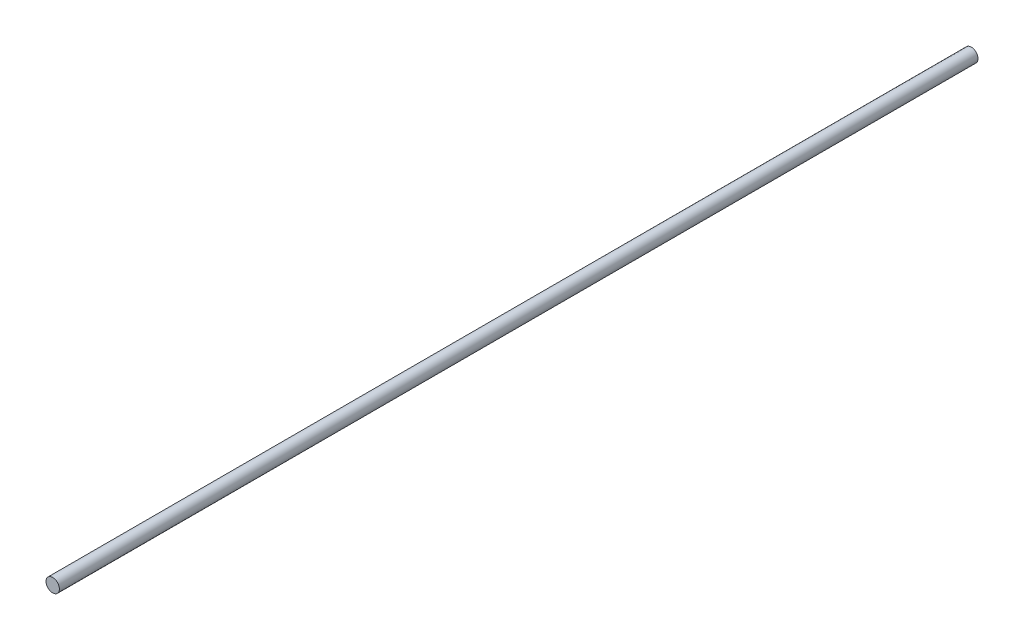
SolidWorks part; units mm, degrees
ref_plane "Спереди" through (0, 0, 0) normal (0, 0, 1) x (1, 0, 0)
ref_plane "Сверху" through (0, 0, 0) normal (0, 1, 0) x (1, 0, 0)
ref_plane "Справа" through (0, 0, 0) normal (1, 0, 0) x (0, 0, -1)
other "Configuration Table"
sketch "Эскиз1" plane through (0, 0, 0) normal (0, 0, 1) x (1, 0, 0)
  circle A0 centre (0, 0) radius 12.5
extrude "Бобышка-Вытянуть1" add sketch "Эскиз1" along normal blind 1712
